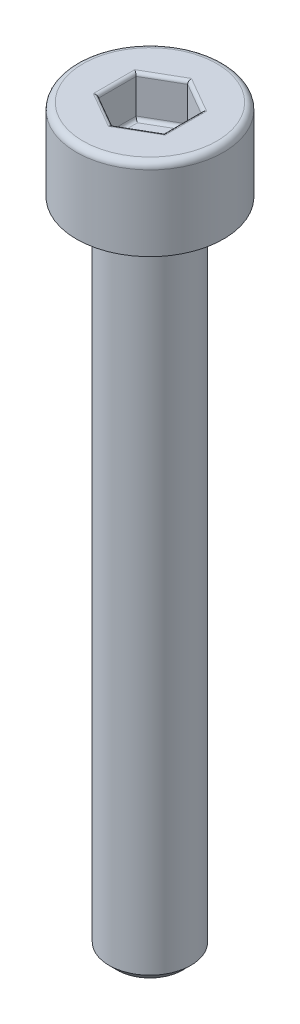
SolidWorks part; units mm, degrees
ref_plane "Front Plane" through (0, 0, 0) normal (0, 0, 1) x (1, 0, 0)
ref_plane "Top Plane" through (0, 0, 0) normal (0, 1, 0) x (1, 0, 0)
ref_plane "Right Plane" through (0, 0, 0) normal (1, 0, 0) x (0, 0, -1)
sketch "Sketch1" plane through (0, 0, 0) normal (0, 0, 1) x (1, 0, 0)
  line L0 (0, 0) -> (0, -47.0967) construction
  line L1 (0, -22.5) -> (-1.25, -22.5)
  line L2 (-1.25, -22.5) -> (-1.25, -2.5)
  line L3 (-1.25, -2.5) -> (-2.25, -2.5)
  line L4 (-2.25, -2.5) -> (-2.25, 0)
  line L5 (-2.25, 0) -> (0, 0)
  line L6 (0, 0) -> (0, -22.5)
  dimension "D1" = 20
  dimension "d" = 2.5
  dimension "k" = 2.5
  dimension "dk" = 4.5
revolve "Revolve1" add sketch "Sketch1" angle 360 about L0
chamfer "Chamfer1" distance 0.25 angle 45 2 edges at (0, -2.5, 1.25) (0, -22.5, 1.25)
fillet "Fillet1" radius 0.2 1 edges at (0, 0, 2.25)
sketch "Sketch2" plane through (0, 0, 0) normal (0, 1, 0) x (1, 0, 0)
  line L1 (0, 1.1547) -> (-1, 0.5774)
  line L2 (-1, 0.5774) -> (-1, -0.5774)
  line L3 (-1, -0.5774) -> (0, -1.1547)
  line L4 (0, -1.1547) -> (1, -0.5774)
  line L5 (1, -0.5774) -> (1, 0.5774)
  line L6 (1, 0.5774) -> (0, 1.1547)
  circle A0 centre (0, 0) radius 1 construction
  dimension "s" = 2
extrude "Cut-Extrude1" cut sketch "Sketch2" against normal blind 1.25
fillet "Fillet2" radius 0.1 12 edges at (-0.5, 0, -0.866) (-1, 0, 0) (-0.5, 0, 0.866) (0.5, 0, 0.866) (1, 0, 0) (0.5, 0, -0.866) (1, -1.25, 0) (0.5, -1.25, 0.866) (-0.5, -1.25, 0.866) (-1, -1.25, 0) (-0.5, -1.25, -0.866) (0.5, -1.25, -0.866)
